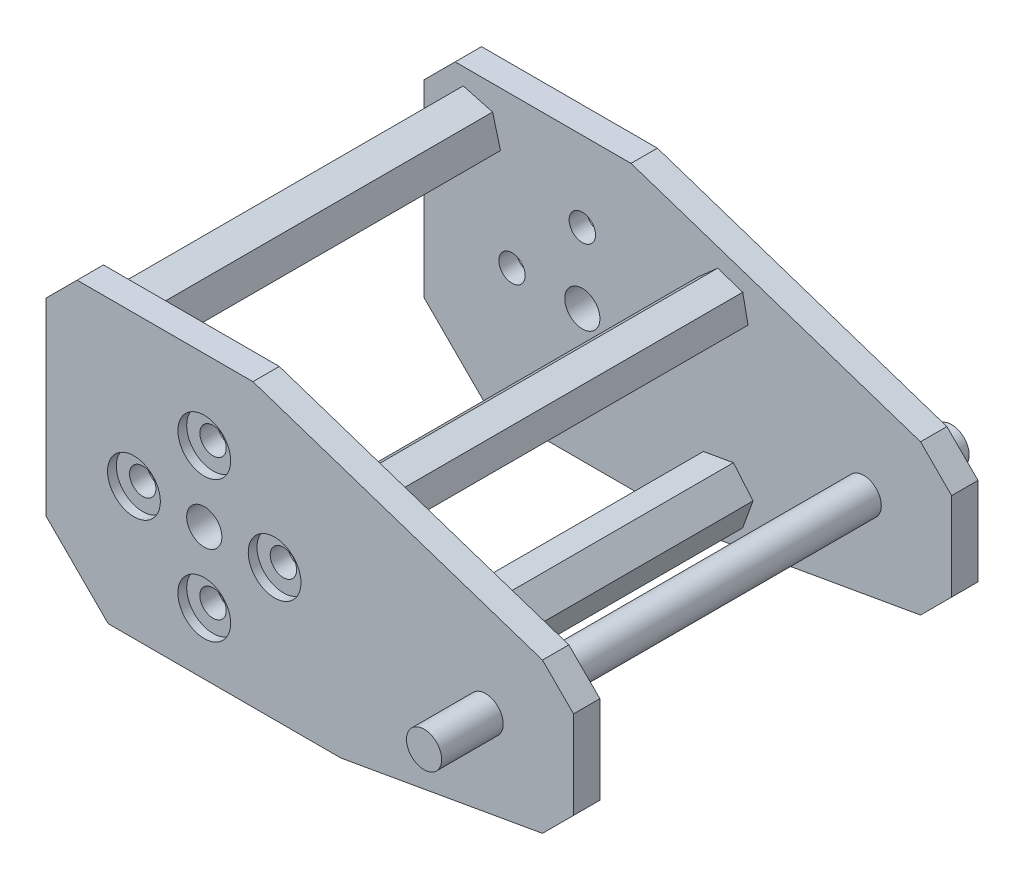
SolidWorks part; units mm, degrees
ref_plane "Front Plane" through (0, 0, 0) normal (0, 0, 1) x (1, 0, 0)
ref_plane "Top Plane" through (0, 0, 0) normal (0, 1, 0) x (1, 0, 0)
ref_plane "Right Plane" through (0, 0, 0) normal (1, 0, 0) x (0, 0, -1)
sketch "Sketch2" plane through (0, 0, 0) normal (0, 0, 1) x (1, 0, 0)
  line L0 (33.5355, -16.0355) -> (3.5355, -16.0355)
  line L1 (3.5355, -16.0355) -> (0, -12.5)
  line L2 (0, -12.5) -> (0, 12.5)
  line L3 (0, 12.5) -> (3.5355, 16.0355)
  line L4 (3.5355, 16.0355) -> (23.5355, 16.0355)
  line L5 (23.5355, 16.0355) -> (56.4645, 5.0785)
  line L6 (56.4645, 5.0785) -> (60, 1.543)
  line L7 (60, 1.543) -> (60, -8.457)
  line L8 (60, -8.457) -> (56.4645, -11.9925)
  line L9 (56.4645, -11.9925) -> (33.5355, -16.0355)
  point P10 (0, 0)
  dimension "D1" = 60
  dimension "D2" = 25
  dimension "D3" = 5
  dimension "D4" = 5
  dimension "D5" = 30
  dimension "D6" = 20
  dimension "D7" = 10
  dimension "D8" = 5
  dimension "D9" = 5
  dimension "D10" = 135
  dimension "D11" = 170
  dimension "D12" = 135
extrude "Boss-Extrude1" add sketch "Sketch2" along normal blind 3
sketch "Sketch4" plane through (0, 0, 0) normal (0, 0, -1) x (-1, 0, 0)
  line L0 (0, 12.5) -> (0, -12.5) construction
  line L1 (-3.5355, -16.0355) -> (-33.5355, -16.0355) construction
  circle A0 centre (-18, -1.0355) radius 2
  point P6 (0, 0)
  dimension "D3" = 4
  dimension "D1" = 18
  dimension "D2" = 15
extrude "Cut-Extrude1" cut sketch "Sketch4" against normal up to surface (3 mm away) up to face at (29.7071, -1.3828, 3)
sketch "Sketch5" plane through (0, 0, 0) normal (0, 0, -1) x (-1, 0, 0)
  line L0 (-18, 0.9645) -> (-18, 6.9645) construction
  line L1 (-26, -1.0355) -> (-18, -1.0355) construction
  circle A0 centre (-18, 6.9645) radius 3
  circle A1 centre (-10, -1.0355) radius 3
  circle A2 centre (-18, -9.0355) radius 3
  circle A3 centre (-26, -1.0355) radius 3
  circle A4 centre (-18, -1.0355) radius 2 construction
  dimension "D1" = 6
  dimension "D6" = 8
  dimension "D7" = 8
  dimension "D2" = 16
  dimension "D3" = 16
  dimension "D4" = 8
  dimension "D5" = 8
extrude "Cut-Extrude2" cut sketch "Sketch5" against normal blind 1
sketch "Sketch6" plane through (0, 0, 1) normal (0, 0, -1) x (-1, 0, 0)
  circle A0 centre (-18, 6.9645) radius 1.5
  circle A1 centre (-26, -1.0355) radius 1.5
  circle A2 centre (-10, -1.0355) radius 1.5
  circle A3 centre (-18, -9.0355) radius 1.5
  dimension "D1" = 3
extrude "Cut-Extrude3" cut sketch "Sketch6" against normal up to surface (2 mm away) up to face at (16, -1.0355, 3)
sketch "Sketch3" plane through (0, 0, 3) normal (0, 0, 1) x (1, 0, 0)
  line L0 (0, 12.5) -> (0, -12.5) construction
  line L2 (8.6921, 9.8784) -> (7.7956, 13.2245)
  line L3 (7.7956, 13.2245) -> (4.4495, 14.1211)
  line L4 (4.4495, 14.1211) -> (2, 11.6716)
  line L5 (2, 11.6716) -> (2.8966, 8.3255)
  line L6 (2.8966, 8.3255) -> (6.2426, 7.4289)
  line L7 (6.2426, 7.4289) -> (8.6921, 9.8784)
  line L8 (3.5355, -16.0355) -> (33.5355, -16.0355) construction
  line L9 (56.4645, 5.0785) -> (23.5355, 16.0355) construction
  line L10 (36.2267, -13.5302) -> (37.4115, -10.275)
  line L11 (37.4115, -10.275) -> (35.1848, -7.6213)
  line L12 (35.1848, -7.6213) -> (31.7733, -8.2228)
  line L13 (31.7733, -8.2228) -> (30.5885, -11.478)
  line L14 (30.5885, -11.478) -> (32.8152, -14.1317)
  line L15 (32.8152, -14.1317) -> (36.2267, -13.5302)
  line L16 (36.8466, 6.7604) -> (36.2436, 9.6992)
  line L17 (36.2436, 9.6992) -> (33.397, 10.6463)
  line L18 (33.397, 10.6463) -> (31.1534, 8.6547)
  line L19 (31.1534, 8.6547) -> (31.7564, 5.716)
  line L20 (31.7564, 5.716) -> (34.603, 4.7688)
  line L21 (34.603, 4.7688) -> (36.8466, 6.7604)
  line L24 (33.5355, -16.0355) -> (56.4645, -11.9925) construction
  line L26 (3.5355, 16.0355) -> (0, 12.5) construction
  circle A0 centre (18, -1.0355) radius 14 construction
  circle A1 centre (5.3461, 10.775) radius 3 construction
  circle A2 centre (34, -10.8765) radius 3 construction
  circle A3 centre (34, 7.7076) radius 2.5981 construction
  point P15 (34.8203, 10.1728)
  dimension "D1" = 18
  dimension "D12" = 28
  dimension "D2" = 2
  dimension "D3" = 6
  dimension "D4" = 2
  dimension "D5" = 15
  dimension "D6" = 6
  dimension "D7" = 2
  dimension "D8" = 34
  dimension "D9" = 6
  dimension "D10" = 2
  dimension "D11" = 34
extrude "Boss-Extrude2" add sketch "Sketch3" along normal blind 40
ref_plane "Plane1" through (0, 0, 23) normal (0, 0, 1) x (1, 0, 0)
mirror "Mirror1" about plane through (0, 0, 23) normal (0, 0, 1) of "Cut-Extrude3", "Cut-Extrude2", "Cut-Extrude1", "Boss-Extrude1"
sketch "Sketch7" plane through (0, 0, 23) normal (0, 0, 1) x (1, 0, 0)
  line L1 (60, -8.457) -> (60, 1.543) construction
  line L3 (50, -3.457) -> (60, -3.457) construction
  circle A1 centre (50, -3.457) radius 2
  dimension "D1" = 10
  dimension "D2" = 4
extrude "Boss-Extrude3" add sketch "Sketch7" along normal blind 30 and the other way blind 30
sketch "Sketch9" plane through (0, 0, 0) normal (0, 0, -1) x (-1, 0, 0)
  line L0 (0, -8.9645) -> (-7.0711, -16.0355)
  line L1 (0, 12.5) -> (0, -12.5) construction
  line L2 (-3.5355, -16.0355) -> (-33.5355, -16.0355) construction
  line L3 (-7.0711, -16.0355) -> (0, -16.0355)
  line L4 (0, -16.0355) -> (0, -8.9645)
  dimension "D1" = 10
  dimension "D2" = 135
extrude "Cut-Extrude5" cut sketch "Sketch9" against normal up to surface (46 mm away) up to face at (52, -3.457, 46)
